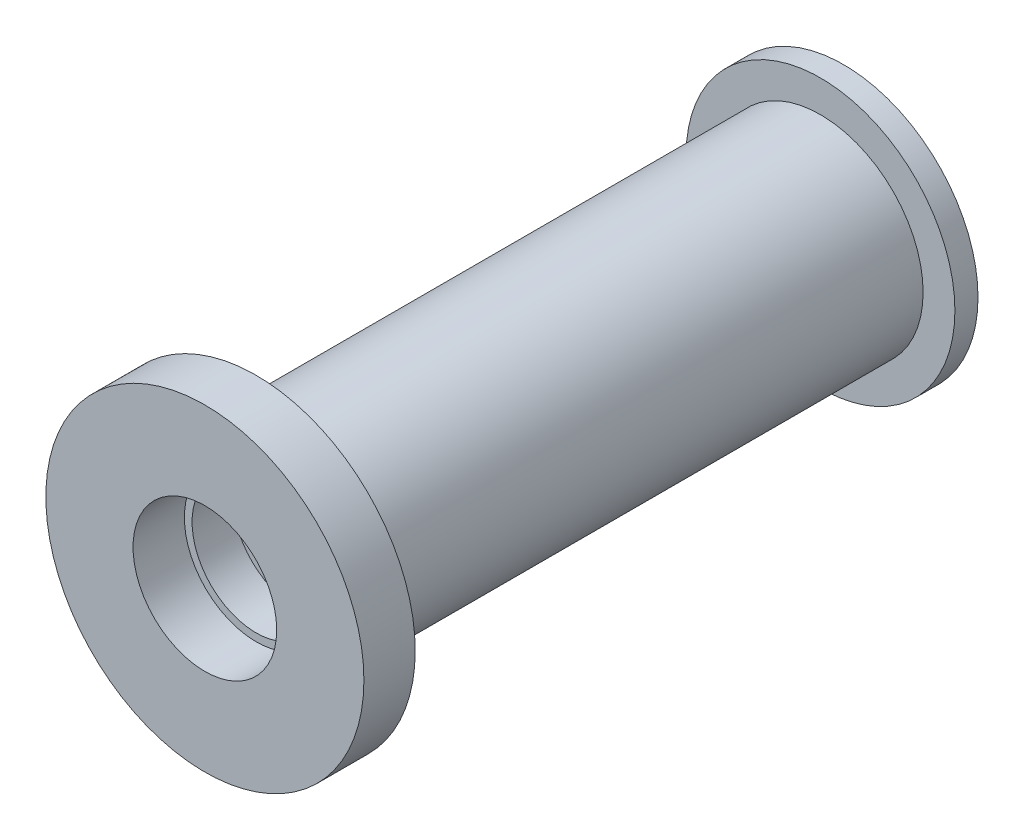
SolidWorks part; units mm, degrees
ref_plane "Front Plane" through (0, 0, 0) normal (0, 0, 1) x (1, 0, 0)
ref_plane "Top Plane" through (0, 0, 0) normal (0, 1, 0) x (1, 0, 0)
ref_plane "Right Plane" through (0, 0, 0) normal (1, 0, 0) x (0, 0, -1)
sketch "S01 - Cord eye liner" plane through (0, 0, 0) normal (0, 0, 1) x (1, 0, 0)
  circle A0 centre (0, 0) radius 2
  circle A1 centre (0, 0) radius 1.1
  dimension "D1" = 2.2
  dimension "D2" = 4
extrude "01 - Cord eye liner" add sketch "S01 - Cord eye liner" along normal blind 11
sketch "S02 - Swaged rear retention lip" plane through (0, 0, 0) normal (0, 0, 1) x (1, 0, 0)
  circle A0 centre (0, 0) radius 2.62
  circle A1 centre (0, 0) radius 1.1
  dimension "D1" = 2.2
  dimension "D2" = 5.24
extrude "02 - Swaged rear retention lip" add sketch "S02 - Swaged rear retention lip" along normal blind 0.45 from offset 0.45
sketch "S03 - Mouth flange" plane through (0, 0, 0) normal (0, 0, 1) x (1, 0, 0)
  circle A0 centre (0, 0) radius 3.1
  circle A1 centre (0, 0) radius 1.4
  dimension "D1" = 2.8
  dimension "D2" = 6.2
extrude "03 - Mouth flange" add sketch "S03 - Mouth flange" along normal blind 1 from offset 11
sketch "S04 - Inlet relief" plane through (0, 0, 0) normal (0, 0, 1) x (1, 0, 0)
  circle A0 centre (0, 0) radius 1.25
  dimension "D1" = 2.5
extrude "04 - Inlet relief" cut sketch "S04 - Inlet relief" along normal blind 0.9 from offset 10.2
